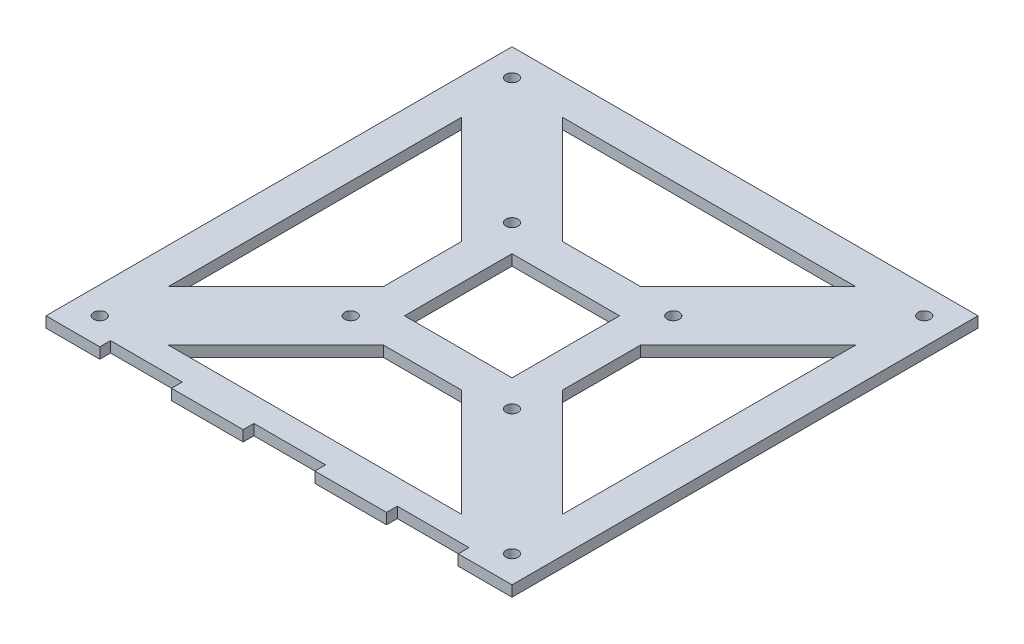
SolidWorks part; units mm, degrees
ref_plane "Front Plane" through (0, 0, 0) normal (0, 0, 1) x (1, 0, 0)
ref_plane "Top Plane" through (0, 0, 0) normal (0, 1, 0) x (1, 0, 0)
ref_plane "Right Plane" through (0, 0, 0) normal (1, 0, 0) x (0, 0, -1)
sketch "Sketch1" plane through (0, 0, 0) normal (0, 1, 0) x (1, 0, 0)
  line L0 (-55, 55) -> (-55, -55)
  line L1 (-65, 65) -> (65, 65)
  line L2 (-65, 65) -> (-65, -65)
  line L3 (-65, -65) -> (65, -65)
  line L4 (65, 65) -> (65, -65)
  line L5 (-65, 65) -> (65, -65) construction
  line L6 (-65, -65) -> (65, 65) construction
  line L7 (-55, -55) -> (55, -55)
  line L8 (55, 55) -> (55, -55)
  line L9 (-55, 55) -> (55, 55)
  line L10 (-15, 15) -> (-15, -15)
  line L11 (-15, -15) -> (15, -15)
  line L12 (15, 15) -> (15, -15)
  line L13 (-15, 15) -> (15, 15)
  line L14 (-25, 25) -> (-25, -25)
  line L15 (-25, -25) -> (25, -25)
  line L16 (25, 25) -> (25, -25)
  line L17 (-25, 25) -> (25, 25)
  line L18 (-55, -55) -> (-25, -25)
  line L19 (-47.9289, -62.0711) -> (-10.8579, -25)
  line L20 (-62.0711, -47.9289) -> (-25, -10.8579)
  line L21 (-62.0711, -47.9289) -> (-32.0711, -17.9289) construction
  line L22 (-47.9289, -62.0711) -> (-17.9289, -32.0711) construction
  line L23 (-47.9289, 62.0711) -> (-10.8579, 25)
  line L24 (-62.0711, 47.9289) -> (-25, 10.8579)
  line L25 (62.0711, 47.9289) -> (25, 10.8579)
  line L26 (47.9289, 62.0711) -> (10.8579, 25)
  line L27 (47.9289, -62.0711) -> (10.8579, -25)
  line L28 (62.0711, -47.9289) -> (25, -10.8579)
  point P0 (0, 0)
  point P39 (0, 0)
  dimension "D1" = 130
  dimension "D2" = 10
  dimension "D3" = 40
  dimension "D4" = 10
  dimension "D5" = 10
  dimension "D6" = 10
  dimension "D7" = 4
extrude "Boss-Extrude1" add sketch "Sketch1" along normal blind 3
sketch "Sketch2" plane through (0, 3, 0) normal (0, 1, 0) x (1, 0, 0)
  line L1 (-57.5, -57.5) -> (57.5, -57.5)
  line L2 (-57.5, -57.5) -> (-57.5, 57.5)
  line L3 (-57.5, 57.5) -> (57.5, 57.5)
  line L4 (57.5, -57.5) -> (57.5, 57.5)
  line L5 (-57.5, -57.5) -> (57.5, 57.5) construction
  line L6 (-57.5, 57.5) -> (57.5, -57.5) construction
  circle A0 centre (-57.5, 57.5) radius 1.7
  circle A1 centre (57.5, 57.5) radius 1.7
  circle A2 centre (57.5, -57.5) radius 1.7
  circle A3 centre (-57.5, -57.5) radius 1.7
  point P0 (0, 0)
  dimension "D2" = 3.4
  dimension "D1" = 115
extrude "Cut-Extrude1" cut sketch "Sketch2" against normal blind 3 contours L3 A0 L2 | L2 A0 L3 | L2 A3 L1 | L1 A3 L2 | L1 A2 L4 | L4 A2 L1 | L4 A1 L3 | L3 A1 L4
sketch "Sketch3" plane through (0, 3, 0) normal (0, 1, 0) x (1, 0, 0)
  line L1 (-22.5, -22.5) -> (22.5, -22.5)
  line L2 (-22.5, -22.5) -> (-22.5, 22.5)
  line L3 (-22.5, 22.5) -> (22.5, 22.5)
  line L4 (22.5, -22.5) -> (22.5, 22.5)
  line L5 (-22.5, -22.5) -> (22.5, 22.5) construction
  line L6 (-22.5, 22.5) -> (22.5, -22.5) construction
  circle A0 centre (-22.5, 22.5) radius 1.7
  circle A1 centre (22.5, 22.5) radius 1.7
  circle A2 centre (22.5, -22.5) radius 1.7
  circle A3 centre (-22.5, -22.5) radius 1.7
  point P0 (0, 0)
  dimension "D2" = 3.4
  dimension "D1" = 45
extrude "Cut-Extrude2" cut sketch "Sketch3" against normal blind 3 contours L2 A3 L1 | L1 A3 L2 | L2 A0 L3 | L3 A0 L2 | L1 A2 L4 | L4 A2 L1 | L4 A1 L3 | L3 A1 L4
sketch "Sketch4" plane through (0, 0, 0) normal (0, -1, 0) x (1, 0, 0)
  line L0 (0, 65) -> (0, 62)
  line L1 (-65, 65) -> (65, 65) construction
  line L2 (-65, 62) -> (65, 62)
  line L3 (65, -65) -> (65, 65) construction
  line L4 (30, 62) -> (30, 65)
  line L5 (-65, 65) -> (65, 65)
  line L6 (-65, 65) -> (-65, 62)
  line L7 (-65, 62) -> (65, 62)
  line L8 (65, 65) -> (65, 62)
  line L9 (-65, 65) -> (65, 62) construction
  line L10 (-65, 62) -> (65, 65) construction
  line L11 (-10, 62) -> (10, 62)
  line L12 (-10, 62) -> (-10, 65)
  line L13 (-10, 65) -> (10, 65)
  line L14 (10, 62) -> (10, 65)
  line L15 (-10, 62) -> (10, 65) construction
  line L16 (-10, 65) -> (10, 62) construction
  line L17 (30, 62) -> (50, 62)
  line L18 (50, 62) -> (50, 65)
  line L19 (30, 65) -> (50, 65)
  line L20 (-50, 62) -> (-50, 65)
  line L21 (-50, 62) -> (-30, 62)
  line L22 (-30, 62) -> (-30, 65)
  line L23 (-50, 65) -> (-30, 65)
  point P9 (0, 62)
  point P10 (0, 63.5)
  point P11 (0, 63.5)
  point P18 (-10, 63.5)
  line M35 (65, 65) -> (-65, 65)
  dimension "D1" = 3
  dimension "D2" = 20
  dimension "D3" = 2
  dimension "D4" = 2
extrude "Cut-Extrude3" cut sketch "Sketch4" against normal blind 10 contours L2 L18 L5 L4 | L2 L14 L5 L0 | L12 L7 L0 M35 | L7 L22 L20 M35
